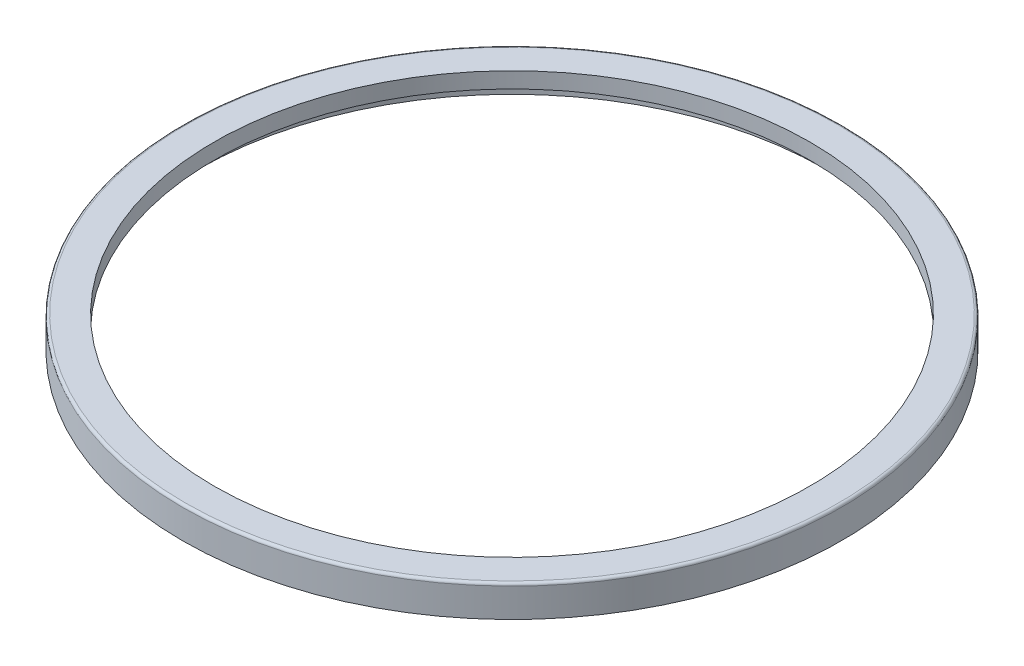
SolidWorks part; units mm, degrees
material "AISI 4340 Steel, annealed"
ref_plane "Front Plane" through (0, 0, 0) normal (0, 0, 1) x (1, 0, 0)
ref_plane "Top Plane" through (0, 0, 0) normal (0, 1, 0) x (1, 0, 0)
ref_plane "Right Plane" through (0, 0, 0) normal (1, 0, 0) x (0, 0, -1)
sketch "Sketch1" plane through (0, 0, 0) normal (0, 0, 1) x (1, 0, 0)
  line L0 (0, 0) -> (-57.564, 0) construction
  line L1 (0, 0) -> (0, 16.6258) construction
  line L2 (-57.564, 0) -> (-63.66, 0)
  line L3 (-63.66, 0) -> (-63.66, -6.096)
  line L4 (-63.66, -6.096) -> (-60.612, -6.096)
  line L5 (-60.612, -6.096) -> (-60.612, -3.048)
  line L6 (-60.612, -3.048) -> (-57.564, -3.048)
  line L7 (-57.564, -3.048) -> (-57.564, 0)
  dimension "D2" = 3.048
  dimension "D3" = 6.096
  dimension "D4" = 3.048
  dimension "D5" = 6.096
  dimension "D6" = 60.612
revolve "Revolve1" add sketch "Sketch1" angle 360 about L1
fillet "Fillet1" radius 1.5875 1 edges at (0, -3.048, -60.612)
fillet "Fillet2" radius 0.508 1 edges at (0, 0, -63.66)
